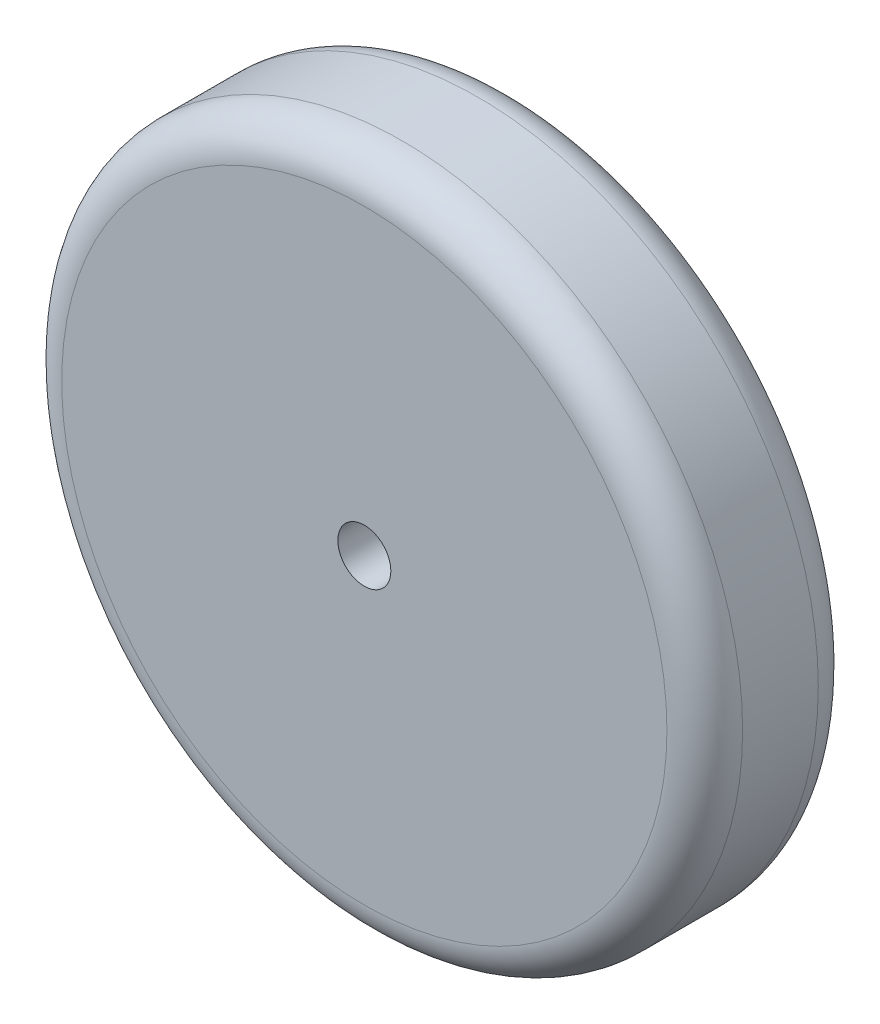
SolidWorks part; units mm, degrees
ref_plane "Front Plane" through (0, 0, 0) normal (0, 0, 1) x (1, 0, 0)
ref_plane "Top Plane" through (0, 0, 0) normal (0, 1, 0) x (1, 0, 0)
ref_plane "Right Plane" through (0, 0, 0) normal (1, 0, 0) x (0, 0, -1)
sketch "Sketch1" plane through (0, 0, 0) normal (0, 0, 1) x (1, 0, 0)
  circle A0 centre (0, 0) radius 45
  circle A1 centre (0, 0) radius 42.5
  circle A2 centre (0, 0) radius 3.5
  dimension "D1" = 90
  dimension "D2" = 85
  dimension "D3" = 7
extrude "Boss-Extrude1" add sketch "Sketch1" along normal blind 20 contours A1 A2 | A0 A1
fillet "Fillet1" radius 5 1 edges at (45, 0, 0)
fillet "Fillet2" radius 5 1 edges at (45, 0, 20)
sketch "Sketch2" plane through (0, 0, 0) normal (0, 0, -1) x (-1, 0, 0)
  line L0 (0, 5) -> (0, 40)
  line L1 (0, 40) -> (13.7116, 37.5765)
  line L2 (13.7116, 37.5765) -> (1.7139, 4.6971)
  line L3 (1.7139, 4.6971) -> (0, 5)
  line L4 (4.1475, 2.7926) -> (2.9389, 4.0451)
  line L5 (2.9389, 4.0451) -> (23.5114, 32.3607)
  line L6 (23.5114, 32.3607) -> (33.1798, 22.3406)
  line L7 (33.1798, 22.3406) -> (4.1475, 2.7926)
  line L8 (4.9968, -0.1786) -> (4.7553, 1.5451)
  line L9 (4.7553, 1.5451) -> (38.0423, 12.3607)
  line L10 (38.0423, 12.3607) -> (39.9745, -1.4287)
  line L11 (39.9745, -1.4287) -> (4.9968, -0.1786)
  line L12 (3.9375, -3.0815) -> (4.7553, -1.5451)
  line L13 (4.7553, -1.5451) -> (38.0423, -12.3607)
  line L14 (38.0423, -12.3607) -> (31.5003, -24.6523)
  line L15 (31.5003, -24.6523) -> (3.9375, -3.0815)
  line L16 (1.3743, -4.8074) -> (2.9389, -4.0451)
  line L17 (2.9389, -4.0451) -> (23.5114, -32.3607)
  line L18 (23.5114, -32.3607) -> (10.994, -38.4595)
  line L19 (10.994, -38.4595) -> (1.3743, -4.8074)
  line L20 (-1.7139, -4.6971) -> (0, -5)
  line L21 (0, -5) -> (0, -40)
  line L22 (0, -40) -> (-13.7116, -37.5765)
  line L23 (-13.7116, -37.5765) -> (-1.7139, -4.6971)
  line L24 (-4.1475, -2.7926) -> (-2.9389, -4.0451)
  line L25 (-2.9389, -4.0451) -> (-23.5114, -32.3607)
  line L26 (-23.5114, -32.3607) -> (-33.1798, -22.3406)
  line L27 (-33.1798, -22.3406) -> (-4.1475, -2.7926)
  line L28 (-4.9968, 0.1786) -> (-4.7553, -1.5451)
  line L29 (-4.7553, -1.5451) -> (-38.0423, -12.3607)
  line L30 (-38.0423, -12.3607) -> (-39.9745, 1.4287)
  line L31 (-39.9745, 1.4287) -> (-4.9968, 0.1786)
  line L32 (-3.9375, 3.0815) -> (-4.7553, 1.5451)
  line L33 (-4.7553, 1.5451) -> (-38.0423, 12.3607)
  line L34 (-38.0423, 12.3607) -> (-31.5003, 24.6523)
  line L35 (-31.5003, 24.6523) -> (-3.9375, 3.0815)
  line L36 (-1.3743, 4.8074) -> (-2.9389, 4.0451)
  line L37 (-2.9389, 4.0451) -> (-23.5114, 32.3607)
  line L38 (-23.5114, 32.3607) -> (-10.994, 38.4595)
  line L39 (-10.994, 38.4595) -> (-1.3743, 4.8074)
  line L40 (0, 0) -> (1.7139, 4.6971) construction
  line L41 (0, 0) -> (4.1475, 2.7926) construction
  circle A0 centre (0, 0) radius 5
  circle A1 centre (0, 0) radius 40 construction
  dimension "D1" = 10
  dimension "D3" = 36
  dimension "D2" = 10
extrude "Cut-Extrude2" cut sketch "Sketch2" against normal blind 6 contours A0 L11 L10 L9 | A0 L15 L14 L13 | A0 L19 L18 L17 | A0 L23 L22 L21 | A0 L27 L26 L25 | A0 L31 L30 L29 | A0 L35 L34 L33 | A0 L39 L38 L37 | A0 L7 L6 L5 | L2 L3 L0 L1
